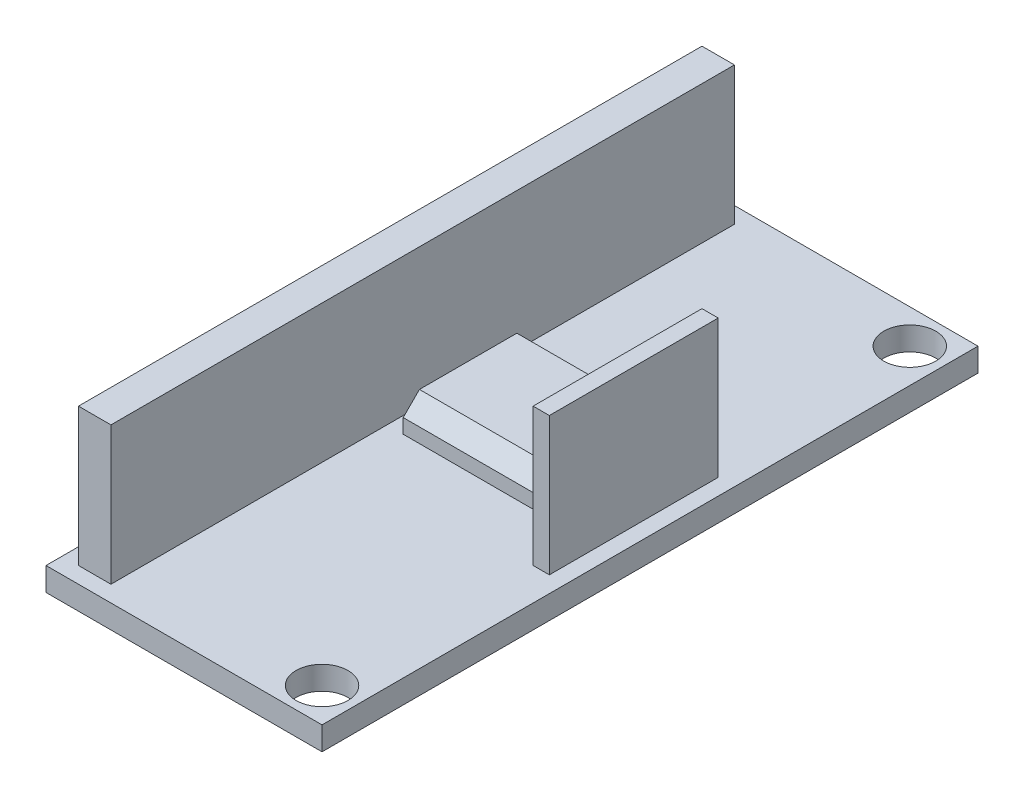
SolidWorks part; units mm, degrees
ref_plane "Front Plane" through (0, 0, 0) normal (0, 0, 1) x (1, 0, 0)
ref_plane "Top Plane" through (0, 0, 0) normal (0, 1, 0) x (1, 0, 0)
ref_plane "Right Plane" through (0, 0, 0) normal (1, 0, 0) x (0, 0, -1)
sketch "Sketch1" plane through (0, 0, 0) normal (0, 1, 0) x (1, 0, 0)
  line L1 (0, 0) -> (17, 0)
  line L2 (0, 0) -> (0, 40.4)
  line L3 (0, 40.4) -> (17, 40.4)
  line L4 (17, 0) -> (17, 40.4)
  dimension "D1" = 40.4
  dimension "D2" = 17
extrude "Boss-Extrude1" add sketch "Sketch1" along normal blind 1.44
sketch "Sketch2" plane through (0, 1.44, 0) normal (0, 1, 0) x (1, 0, 0)
  line L0 (17, 40.4) -> (0, 40.4) construction
  line L1 (17, 0) -> (17, 40.4) construction
  line L2 (0, 0) -> (17, 0) construction
  circle A0 centre (14.9, 38.3) radius 1.6
  circle A1 centre (14.9, 2.1) radius 1.6
  dimension "D1" = 3.2
  dimension "D2" = 2.1
  dimension "D3" = 2.1
  dimension "D4" = 3.2
  dimension "D5" = 2.1
  dimension "D6" = 2.1
extrude "Cut-Extrude1" cut sketch "Sketch2" against normal blind 1.44
sketch "Sketch3" plane through (0, 1.44, 0) normal (0, 1, 0) x (1, 0, 0)
  line L0 (0, 40.4) -> (0, 0) construction
  line L1 (4, 26) -> (14, 26)
  line L2 (4, 26) -> (4, 18)
  line L3 (4, 18) -> (14, 18)
  line L4 (14, 26) -> (14, 18)
  line L5 (0, 0) -> (17, 0) construction
  dimension "D1" = 10
  dimension "D2" = 8
  dimension "D3" = 4
  dimension "D4" = 18
extrude "Boss-Extrude2" add sketch "Sketch3" along normal blind 1.89
chamfer "Chamfer1" distance 1 angle 45 2 edges at (9, 3.33, -26) (9, 3.33, -18)
sketch "Sketch4" plane through (0, 1.44, 0) normal (0, 1, 0) x (1, 0, 0)
  line L0 (0, 0) -> (17, 0) construction
  line L1 (1, 39.4) -> (3, 39.4)
  line L2 (1, 39.4) -> (1, 1)
  line L3 (1, 1) -> (3, 1)
  line L4 (3, 39.4) -> (3, 1)
  line L5 (17, 40.4) -> (0, 40.4) construction
  line L6 (0, 40.4) -> (0, 0) construction
  line L7 (4, 26) -> (4, 18) construction
  line L8 (14, 18) -> (14, 26) construction
  line L9 (16, 25.4) -> (15, 25.4)
  line L10 (16, 25.4) -> (16, 15)
  line L11 (16, 15) -> (15, 15)
  line L12 (15, 25.4) -> (15, 15)
  line L13 (17, 0) -> (17, 40.4) construction
  dimension "D1" = 1
  dimension "D2" = 1
  dimension "D3" = 1
  dimension "D4" = 1
  dimension "D5" = 1
  dimension "D6" = 1
  dimension "D7" = 15
  dimension "D8" = 15
extrude "Boss-Extrude3" add sketch "Sketch4" along normal blind 8.5
